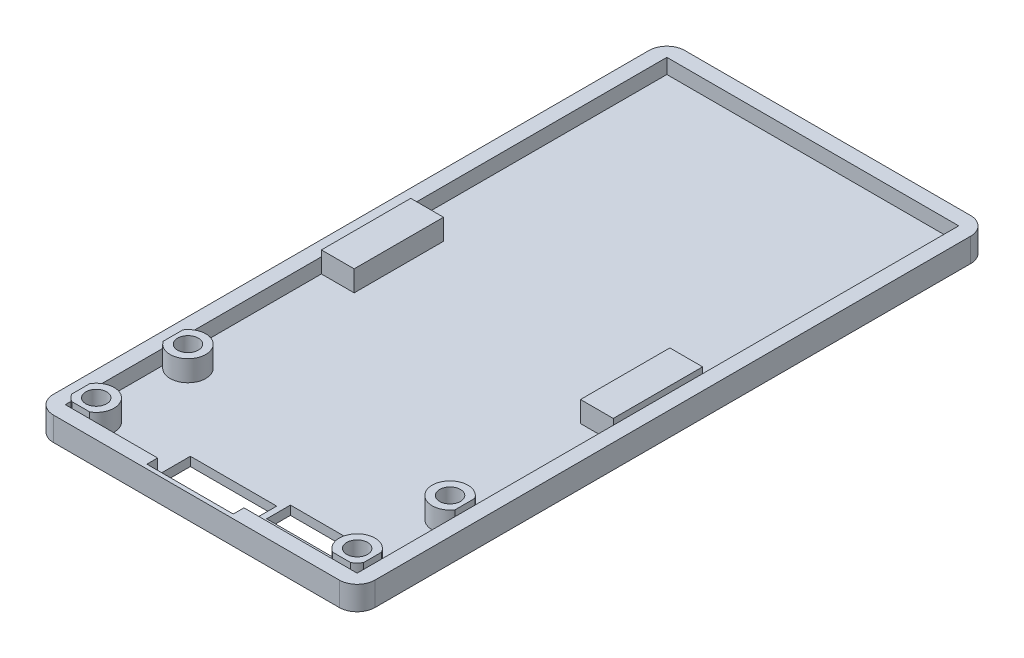
SolidWorks part; units mm, degrees
ref_plane "Front Plane" through (0, 0, 0) normal (0, 0, 1) x (1, 0, 0)
ref_plane "Top Plane" through (0, 0, 0) normal (0, 1, 0) x (1, 0, 0)
ref_plane "Right Plane" through (0, 0, 0) normal (1, 0, 0) x (0, 0, -1)
sketch "Sketch1" plane through (0, 0, 0) normal (0, 1, 0) x (1, 0, 0)
  line L1 (-24.5, -50.5) -> (24.5, -50.5)
  line L2 (-24.5, -50.5) -> (-24.5, 50.5)
  line L3 (-24.5, 50.5) -> (24.5, 50.5)
  line L4 (24.5, -50.5) -> (24.5, 50.5)
  line L5 (-24.5, -50.5) -> (24.5, 50.5) construction
  line L6 (-24.5, 50.5) -> (24.5, -50.5) construction
  point P0 (0, 0)
  dimension "D1" = 49
  dimension "D2" = 101
extrude "Boss-Extrude1" add sketch "Sketch1" along normal blind 1.5
sketch "Sketch2" plane through (0, 0, 0) normal (0, 1, 0) x (1, 0, 0)
  line L4 (24.5, -50.5) -> (24.5, 50.5)
  line L5 (24.5, 50.5) -> (-24.5, 50.5)
  line L6 (-24.5, 50.5) -> (-24.5, -50.5)
  line L7 (-24.5, -50.5) -> (24.5, -50.5)
  line L8 (24.5, -50.5) -> (24.5, 50.5)
  line L9 (24.5, 50.5) -> (-24.5, 50.5)
  line L10 (-24.5, 50.5) -> (-24.5, -50.5)
  line L11 (-24.5, -50.5) -> (24.5, -50.5)
  line L16 (27, -53) -> (27, 53)
  line L17 (27, 53) -> (-27, 53)
  line L18 (-27, 53) -> (-27, -53)
  line L19 (-27, -53) -> (27, -53)
  line L20 (27, -53) -> (27, 53)
  line L21 (27, 53) -> (-27, 53)
  line L22 (-27, 53) -> (-27, -53)
  line L23 (-27, -53) -> (27, -53)
  dimension "D1" = 0
  dimension "D2" = 2.5
extrude "Boss-Extrude2" add sketch "Sketch2" along normal blind 4
sketch "Sketch3" plane through (0, 0, 0) normal (0, 1, 0) x (1, 0, 0)
  line L0 (24.5, -50.5) -> (-24.5, -50.5) construction
  line L1 (-24.5, -50.5) -> (-24.5, 50.5) construction
  line L2 (-24.5, 50.5) -> (-24.5, -50.5) construction
  line L3 (-24.5, -30.7417) -> (-24.5, -34.0583)
  line L4 (-24.5, -7.5) -> (-19, -7.5)
  line L5 (-24.5, -7.5) -> (-24.5, 7.5)
  line L6 (-24.5, 7.5) -> (-19, 7.5)
  line L7 (-19, -7.5) -> (-19, 7.5)
  line L8 (-24.5, -46.4033) -> (-24.5, -49.3967)
  line L9 (-24.5, 50.5) -> (-24.5, -50.5) construction
  line L10 (-23.3967, -50.5) -> (-20.4033, -50.5)
  line L11 (-24.5, -50.5) -> (24.5, -50.5) construction
  arc A0 (-24.5, -49.3967) -> (-23.3967, -50.5) centre (-21.9, -47.9) ccw
  arc A1 (-24.5, -34.0583) -> (-24.5, -30.7417) centre (-22, -32.4) ccw
  arc A2 (-20.4033, -50.5) -> (-24.5, -46.4033) centre (-21.9, -47.9) ccw
  point P15 (-19, 0)
  dimension "D2" = 2.6
  dimension "D5" = 6
  dimension "D7" = 6
  dimension "D1" = 2.6
  dimension "D3" = 2.5
  dimension "D4" = 18.1
  dimension "D6" = 15
extrude "Boss-Extrude3" add sketch "Sketch3" along normal offset from surface (5 mm away) 1 up to face at (0, 4, 0) offset beyond the face yes
mirror "Mirror1" about plane through (0, 0, 0) normal (1, 0, 0) of "Boss-Extrude3"
sketch "Sketch4" plane through (0, 5, 0) normal (0, 1, 0) x (1, 0, 0)
  circle A0 centre (-21.9, -47.9) radius 1.75
  circle A1 centre (21.9, -47.9) radius 1.75
  dimension "D1" = 3.5
  dimension "D2" = 3.5
extrude "Cut-Extrude1" cut sketch "Sketch4" against normal blind 4.25
sketch "Sketch5" plane through (0, 5, 0) normal (0, 1, 0) x (1, 0, 0)
  circle A0 centre (-22, -32.4) radius 1.75
  circle A1 centre (22, -32.4) radius 1.75
  dimension "D1" = 3.5
  dimension "D2" = 3.5
extrude "Cut-Extrude2" cut sketch "Sketch5" against normal blind 4.25
sketch "Sketch6" plane through (0, 0, 0) normal (0, 1, 0) x (1, 0, 0)
  line L1 (-9, -45) -> (5.5, -45)
  line L2 (-9, -45) -> (-9, -52.3)
  line L3 (-9, -52.3) -> (5.5, -52.3)
  line L4 (5.5, -45) -> (5.5, -52.3)
  line L8 (-23.3967, -50.5) -> (20.4033, -50.5) construction
  line L10 (24.5, -46.4033) -> (24.5, -34.0583) construction
  line L11 (-24.5, -34.0583) -> (-24.5, -46.4033) construction
  line L13 (-27, -53) -> (27, -53) construction
  dimension "D1" = 15.5
  dimension "D2" = 19
  dimension "D3" = 0.7
  dimension "D4" = 5.5
extrude "Cut-Extrude3" cut sketch "Sketch6" along normal through all
sketch "Sketch7" plane through (0, 0, 0) normal (0, 1, 0) x (1, 0, 0)
  line L0 (-27, -53) -> (27, -53) construction
  line L1 (18.3, -47.7) -> (6.5, -47.7)
  line L2 (18.3, -47.7) -> (18.3, -43.7)
  line L3 (18.3, -43.7) -> (6.5, -43.7)
  line L4 (6.5, -47.7) -> (6.5, -43.7)
  line L6 (-27, -53) -> (27, -53) construction
  line L7 (27, -53) -> (27, 53) construction
  point P10 (12.4, -43.7)
  dimension "D1" = 11.8
  dimension "D3" = 9.3
  dimension "D4" = 5.3
  dimension "D5" = 14.6
extrude "Cut-Extrude4" cut sketch "Sketch7" along normal through all
fillet "Fillet1" radius 3 4 edges at (-27, 2, 53) (27, 2, 53) (27, 2, -53) (-27, 2, -53)
